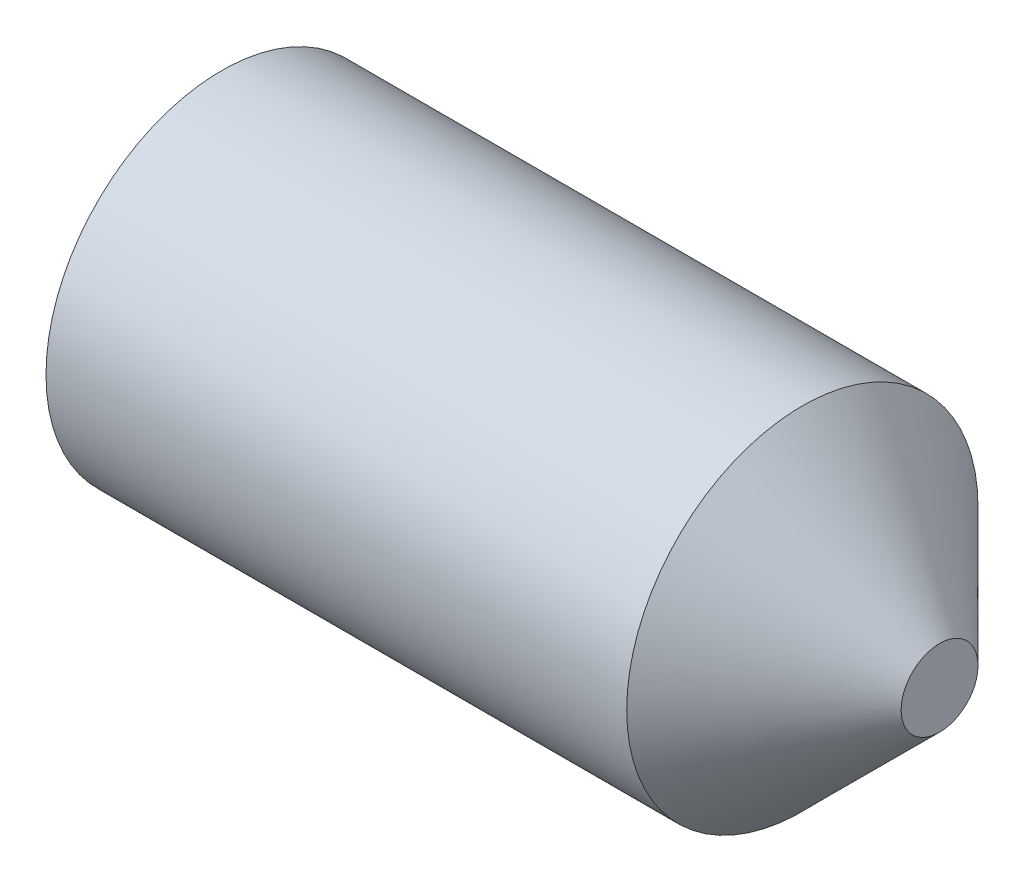
SolidWorks part; units mm, degrees
revolve "BaseBody" add sketch "BodySke" angle 360 about L5
sketch "BodySke" plane through (0, 0, 0) normal (0, 0, 1) x (1, 0, 0)
  line L0 (0, 0) -> (0, 10.352)
  line L1 (0, 10.352) -> (0.9515, 12)
  line L2 (0.9515, 12) -> (40.625, 12)
  line L3 (40.625, 12) -> (50, 2.625)
  line L4 (50, 0) -> (0, 0)
  line L5 (-12.7, 0) -> (88.9, 0) construction
  line L6 (50, 2.625) -> (50, 0)
  line L7 (50, 2.625) -> (50, 12.15) construction
  line L8 (0, -10.352) -> (0.9515, -12) construction
  line L9 (3, 15.875) -> (3, -3.175) construction
  line L10 (40.625, -12) -> (50, -2.625) construction
  dimension "Diameter" = 24
  dimension "Drive_ch_ang" = 60
  dimension "Minor_dia" = 20.704
  dimension "Tip_dia" = 5.25
  dimension "Length" = 50
  dimension "Advance" = 3
  dimension "Cone_ang" = 90
cosmetic thread "ThreadCosmetic" [suppressed] parameters "Thread_minor"=20.704
ref_plane "Plane1" through (0, 0, 0) normal (0, 0, 1) x (1, 0, 0)
ref_plane "Plane2" through (0, 0, 0) normal (0, 1, 0) x (1, 0, 0)
ref_plane "Plane3" through (0, 0, 0) normal (1, 0, 0) x (0, 0, -1)
sketch "Sketch2" plane through (0, 0, 0) normal (-1, 0, 0) x (0, 0, 1)
  line L0 (3.4641, 6) -> (-3.4641, 6)
  line L1 (-3.4641, 6) -> (-6.9282, 0)
  line L2 (3.4641, 6) -> (6.9282, 0)
  line L3 (3.4641, -6) -> (6.9282, 0)
  line L4 (3.4641, -6) -> (-3.4641, -6)
  line L5 (-3.4641, -6) -> (-6.9282, 0)
  dimension "Hex_size" = 12
  dimension "D2" = 6
  dimension "D3" = 6
extrude "Hex" cut sketch "Sketch2" against normal blind 15
sketch "ThdSchSke" [suppressed] plane through (0, 0, 0) normal (0, 0, 1) x (1, 0, 0)
  line L0 (0.9515, -10.352) -> (-0.2025, -12)
  line L1 (0.9515, -10.352) -> (2.1054, -12)
  line L2 (2.1054, -12) -> (2.1054, -15)
  line L3 (-3.175, 0) -> (5.1513, 0) construction
  line L5 (2.1054, -15) -> (-0.2025, -15)
  line L6 (-0.2025, -15) -> (-0.2025, -12)
  line L8 (0.9515, 12) -> (0.9515, -12) construction
  dimension "Thread_minor" = 20.704
  dimension "Diameter" = 24
revolve "ThreadSchematic" [suppressed] cut sketch "ThdSchSke" angle 360 about L3
pattern_linear "ThdSchPat" [suppressed]
equation "\"D2@Sketch2\" = \"Hex_size@Sketch2\" / 2"
equation "\"D3@Sketch2\" = \"Hex_size@Sketch2\" / 2"
equation "\"Thread_minor@ThreadCosmetic\" = \"Minor_dia@BodySke\""
equation "\"Thread_minor@ThdSchSke\" = \"Thread_minor@ThreadCosmetic\""
equation "\"Diameter@ThdSchSke\" = \"Diameter@BodySke\""
equation "\"Overcut@ThdSchSke\" = \"Diameter@BodySke\" * 1.25"
equation "\"Num_threads@ThdSchPat\" = int( (\"Length@BodySke\" - ( ( ( \"Diameter@BodySke\" - \"Minor_dia@BodySke\" ) * 0.5 ) / tan( \"Drive_ch_ang@BodySke\" * 0.017453292 ) ) - ( ( ( \"Diameter@BodySke\" - \"Tip_dia@BodySke\" ) * 0.5 ) / tan( \"Cone_ang@BodySke\" / 2.0 * 0.017453292 ) ) ) / \"Advance@BodySke\" + 0.999 )  + 1"
equation "\"Advance@ThdSchPat\" = (\"Length@BodySke\" - ( ( ( \"Diameter@BodySke\" - \"Minor_dia@BodySke\" ) * 0.5 ) / tan( \"Drive_ch_ang@BodySke\" * 0.017453292 ) ) - ( ( ( \"Diameter@BodySke\" - \"Tip_dia@BodySke\" ) * 0.5 ) / tan( \"Cone_ang@BodySke\" / 2.0 * 0.017453292 ) ) ) /  (\"Num_threads@ThdSchPat\" - 1) 'relax it"
equation "' \"Num_threads@ThdSchPat\" = \"Num_threads@ThdSchPat\" - sgn( \"Num_threads@ThdSchPat\" - 1) '---chamfered tips only---"
